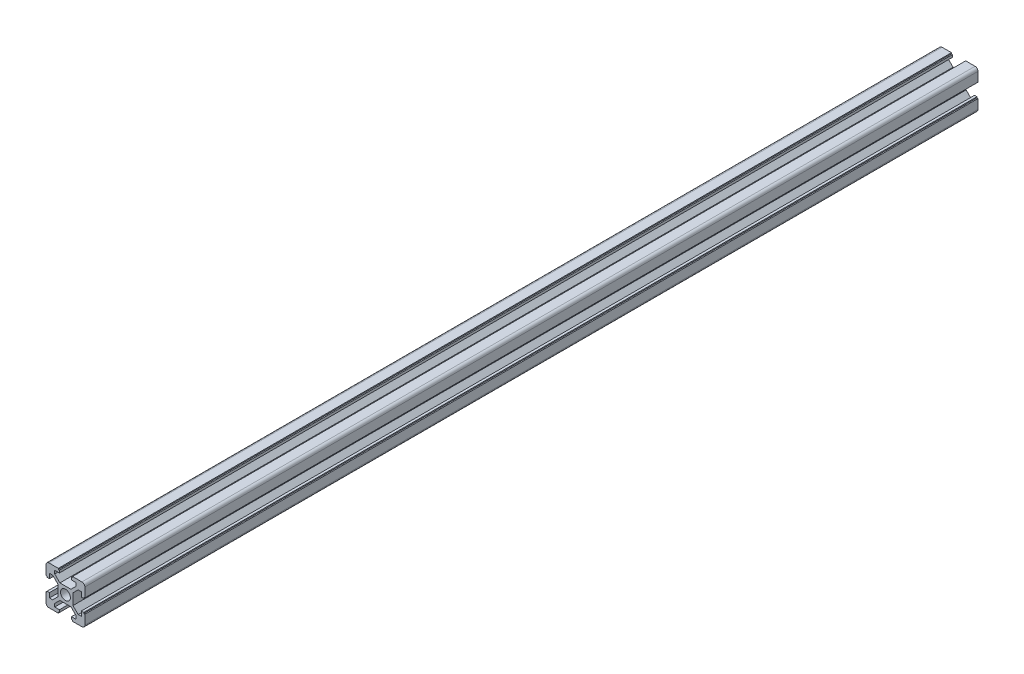
SolidWorks part; units mm, degrees
material "1060 Alloy"
ref_plane "Front Plane" through (0, 0, 0) normal (0, 0, 1) x (1, 0, 0)
ref_plane "Top Plane" through (0, 0, 0) normal (0, 1, 0) x (1, 0, 0)
ref_plane "Right Plane" through (0, 0, 0) normal (1, 0, 0) x (0, 0, -1)
sketch "Sketch2" plane through (0, 0, 0) normal (0, 0, 1) x (1, 0, 0)
  line L0 (-10, 10) -> (-3.65, 10)
  line L7 (-3.65, 10) -> (-3.65, 9.45)
  line L8 (-3.65, 9.45) -> (-3.1, 9.45)
  line L9 (-3.1, 9.45) -> (-3.1, 8.2)
  line L10 (-3.1, 8.2) -> (-5.5, 8.2)
  line L11 (-5.5, 8.2) -> (-5.5, 6.5607)
  line L18 (0, 0) -> (-10, 10) construction
  line L20 (-2.8393, 3.9) -> (-5.5, 6.5607)
  line L21 (-2.8393, 3.9) -> (0, 3.9)
  line L22 (-3.9, 2.8393) -> (-3.9, 0)
  line L23 (-3.9, 2.8393) -> (-6.5607, 5.5)
  line L24 (-8.2, 5.5) -> (-6.5607, 5.5)
  line L25 (-8.2, 3.1) -> (-8.2, 5.5)
  line L26 (-9.45, 3.1) -> (-8.2, 3.1)
  line L27 (-9.45, 3.65) -> (-9.45, 3.1)
  line L28 (-10, 3.65) -> (-9.45, 3.65)
  line L29 (-10, 10) -> (-10, 3.65)
  line L30 (2.8393, 3.9) -> (0, 3.9)
  line L31 (2.8393, 3.9) -> (5.5, 6.5607)
  line L32 (5.5, 8.2) -> (5.5, 6.5607)
  line L33 (3.1, 8.2) -> (5.5, 8.2)
  line L34 (3.1, 9.45) -> (3.1, 8.2)
  line L35 (3.65, 9.45) -> (3.1, 9.45)
  line L36 (10, 10) -> (3.65, 10)
  line L37 (10, 10) -> (10, 3.65)
  line L38 (10, 3.65) -> (9.45, 3.65)
  line L39 (9.45, 3.65) -> (9.45, 3.1)
  line L40 (9.45, 3.1) -> (8.2, 3.1)
  line L41 (8.2, 3.1) -> (8.2, 5.5)
  line L42 (8.2, 5.5) -> (6.5607, 5.5)
  line L43 (3.9, 2.8393) -> (6.5607, 5.5)
  line L44 (3.9, 2.8393) -> (3.9, 0)
  line L45 (3.65, 10) -> (3.65, 9.45)
  line L46 (3.9, -2.8393) -> (3.9, 0)
  line L47 (3.9, -2.8393) -> (6.5607, -5.5)
  line L48 (8.2, -5.5) -> (6.5607, -5.5)
  line L49 (8.2, -3.1) -> (8.2, -5.5)
  line L50 (9.45, -3.1) -> (8.2, -3.1)
  line L51 (9.45, -3.65) -> (9.45, -3.1)
  line L52 (10, -10) -> (10, -3.65)
  line L53 (10, -10) -> (3.65, -10)
  line L54 (3.65, -10) -> (3.65, -9.45)
  line L55 (3.65, -9.45) -> (3.1, -9.45)
  line L56 (3.1, -9.45) -> (3.1, -8.2)
  line L57 (3.1, -8.2) -> (5.5, -8.2)
  line L58 (5.5, -8.2) -> (5.5, -6.5607)
  line L59 (2.8393, -3.9) -> (5.5, -6.5607)
  line L60 (2.8393, -3.9) -> (0, -3.9)
  line L61 (10, -3.65) -> (9.45, -3.65)
  line L62 (-2.8393, -3.9) -> (0, -3.9)
  line L63 (-2.8393, -3.9) -> (-5.5, -6.5607)
  line L64 (-5.5, -8.2) -> (-5.5, -6.5607)
  line L65 (-3.1, -8.2) -> (-5.5, -8.2)
  line L66 (-3.1, -9.45) -> (-3.1, -8.2)
  line L67 (-3.65, -9.45) -> (-3.1, -9.45)
  line L68 (-10, -10) -> (-3.65, -10)
  line L69 (-10, -10) -> (-10, -3.65)
  line L70 (-10, -3.65) -> (-9.45, -3.65)
  line L71 (-9.45, -3.65) -> (-9.45, -3.1)
  line L72 (-9.45, -3.1) -> (-8.2, -3.1)
  line L73 (-8.2, -3.1) -> (-8.2, -5.5)
  line L74 (-8.2, -5.5) -> (-6.5607, -5.5)
  line L75 (-3.9, -2.8393) -> (-6.5607, -5.5)
  line L76 (-3.9, -2.8393) -> (-3.9, 0)
  line L77 (-3.65, -10) -> (-3.65, -9.45)
  dimension "D1" = 10
  dimension "D2" = 5.5
  dimension "D3" = 1.8
  dimension "D4" = 6.1
  dimension "D5" = 0.55
  dimension "D6" = 0.55
  dimension "D7" = 2.4
  dimension "D8" = 135
  dimension "D9" = 4
  dimension "D10" = 0.75
extrude "Boss-Extrude1" add sketch "Sketch2" against normal blind 460
sketch "Sketch3" plane through (0, 0, 0) normal (0, 0, 1) x (1, 0, 0)
  circle A0 centre (0, 0) radius 2.55
extrude "Cut-Extrude1" cut sketch "Sketch3" against normal through all contours A0
fillet "Fillet1" radius 1.5 4 edges at (-10, -10, -230) (10, -10, -230) (-10, 10, -230) (10, 10, -230)
